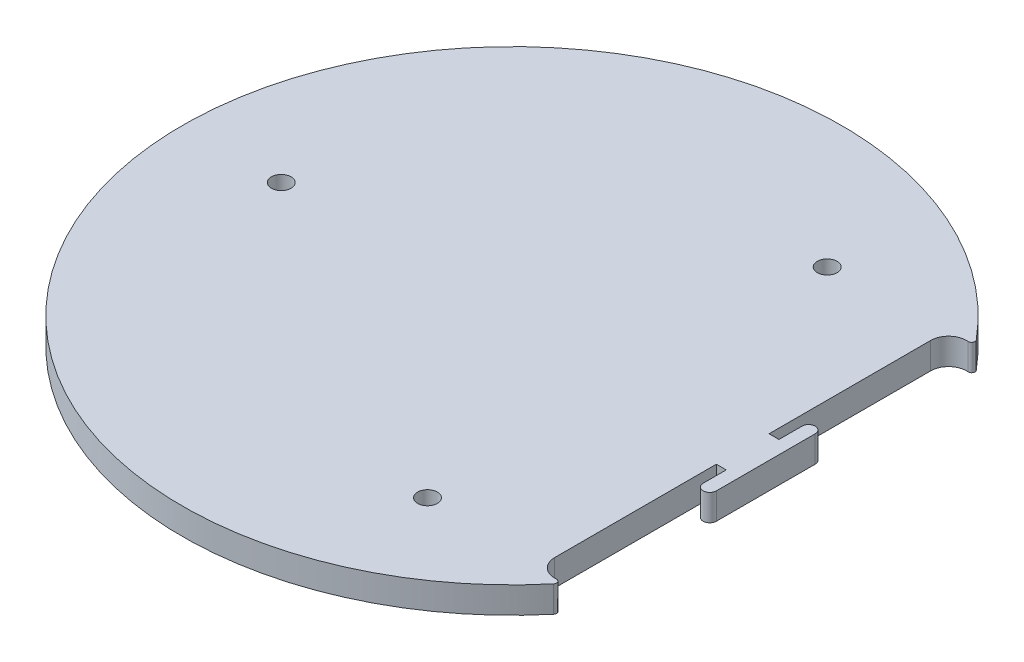
SolidWorks part; units mm, degrees
ref_plane "Alzado" through (0, 0, 0) normal (0, 0, 1) x (1, 0, 0)
ref_plane "Planta" through (0, 0, 0) normal (0, 1, 0) x (1, 0, 0)
ref_plane "Vista lateral" through (0, 0, 0) normal (1, 0, 0) x (0, 0, -1)
sketch "Croquis1" plane through (0, 0, 0) normal (0, 1, 0) x (1, 0, 0)
  line L0 (-50, 0) -> (35, 0) construction
  line L1 (36.5, -28.5161) -> (36.5, -4) construction
  line L2 (37.5, -28.5161) -> (37.5, 28.5161) construction
  line L3 (35, -28.5161) -> (35, -4)
  line L4 (37.5, 0) -> (36.5, 0) construction
  line L5 (37.5, 7.5) -> (36.5, 7.5) construction
  line L6 (37.5, -6.5) -> (36.5, -6.5) construction
  line L7 (37.5, -7.5) -> (37.5, 7.5) construction
  line L8 (36.5, -7.5) -> (36.5, -4)
  line L9 (38.5, -7.5) -> (38.5, 7.5)
  line L10 (-50, -4) -> (35, -4) construction
  line L11 (-50, 4) -> (35, 4) construction
  line L12 (35, 4) -> (36.5, 4)
  line L13 (35, -4) -> (36.5, -4)
  line L14 (35, 4) -> (35, 28.5161)
  line L15 (35, -28.5161) -> (35, 28.5161) construction
  line L16 (36.5, 4) -> (36.5, 28.5161) construction
  line L17 (36.5, -28.5161) -> (36.5, 28.5161) construction
  line L18 (36.5, 7.5) -> (36.5, 4)
  arc A0 (38.3792, 32.0474) -> (38.3792, -32.0474) centre (0, 0) ccw
  arc A1 (36.5, -7.5) -> (38.5, -7.5) centre (37.5, -7.5) ccw
  arc A2 (37.9494, 31.2228) -> (35, 28.5161) centre (37.7167, 28.5161) ccw
  arc A3 (37.9494, 31.2228) -> (38.3792, 32.0474) centre (37.9926, 31.7246) ccw
  arc A4 (37.9494, -31.2228) -> (38.3792, -32.0474) centre (37.9926, -31.7246) cw
  arc A5 (37.9494, -31.2228) -> (35, -28.5161) centre (37.7167, -28.5161) cw
  arc A6 (38.5, 7.5) -> (36.5, 7.5) centre (37.5, 7.5) ccw
  point P25 (37.5, 0)
  dimension "D1" = 100
  dimension "D2" = 1.5
  dimension "D3" = 85
  dimension "D5" = 14
  dimension "D4" = 1
  dimension "D6" = 4
  dimension "D7" = 4
extrude "Saliente-Extruir1" add sketch "Croquis1" along normal mid plane 4
sketch "Croquis2" plane through (0, -2, 0) normal (0, -1, 0) x (1, 0, 0)
  line L0 (0, 0) -> (37.7172, 65.3282) construction
  line L1 (0, 0) -> (37.7172, -65.3282) construction
  line L3 (0, 0) -> (-75.4345, 0) construction
  arc A0 (38.3792, 32.0474) -> (38.3792, -32.0474) centre (0, 0) ccw construction
  arc A1 (38.3792, 32.0474) -> (38.3792, -32.0474) centre (0, 0) ccw
  arc A2 (26.8654, 22.4332) -> (26.8654, -22.4332) centre (0, 0) ccw construction
  circle A3 centre (17.5, 30.3109) radius 1.5
  circle A4 centre (-35, 0) radius 1.5
  circle A5 centre (17.5, -30.3109) radius 1.5
  point P4 (17.5, 30.3109)
  point P5 (17.5, -30.3109)
  point P19 (0, 0)
  dimension "D2" = 3
  dimension "D1" = 15
  dimension "D3" = 3
extrude "Cortar-Extruir1" cut sketch "Croquis2" against normal blind 7 contours A4 | A5 | A3
sketch "Croquis3" plane through (0, -2, 0) normal (0, -1, 0) x (1, 0, 0)
  circle A3 centre (17.5, 30.3109) radius 3
  circle A4 centre (17.5, -30.3109) radius 3
  circle A5 centre (-35, 0) radius 3
  circle A6 centre (-35, 0) radius 4
  circle A7 centre (17.5, 30.3109) radius 4
  circle A8 centre (17.5, -30.3109) radius 4
  circle A9 centre (17.5, 30.3109) radius 1.5 construction
  circle A10 centre (17.5, -30.3109) radius 1.5 construction
  dimension "D1" = 8
  dimension "D2" = 6
extrude "Saliente-Extruir2" add sketch "Croquis3" along normal blind 5
